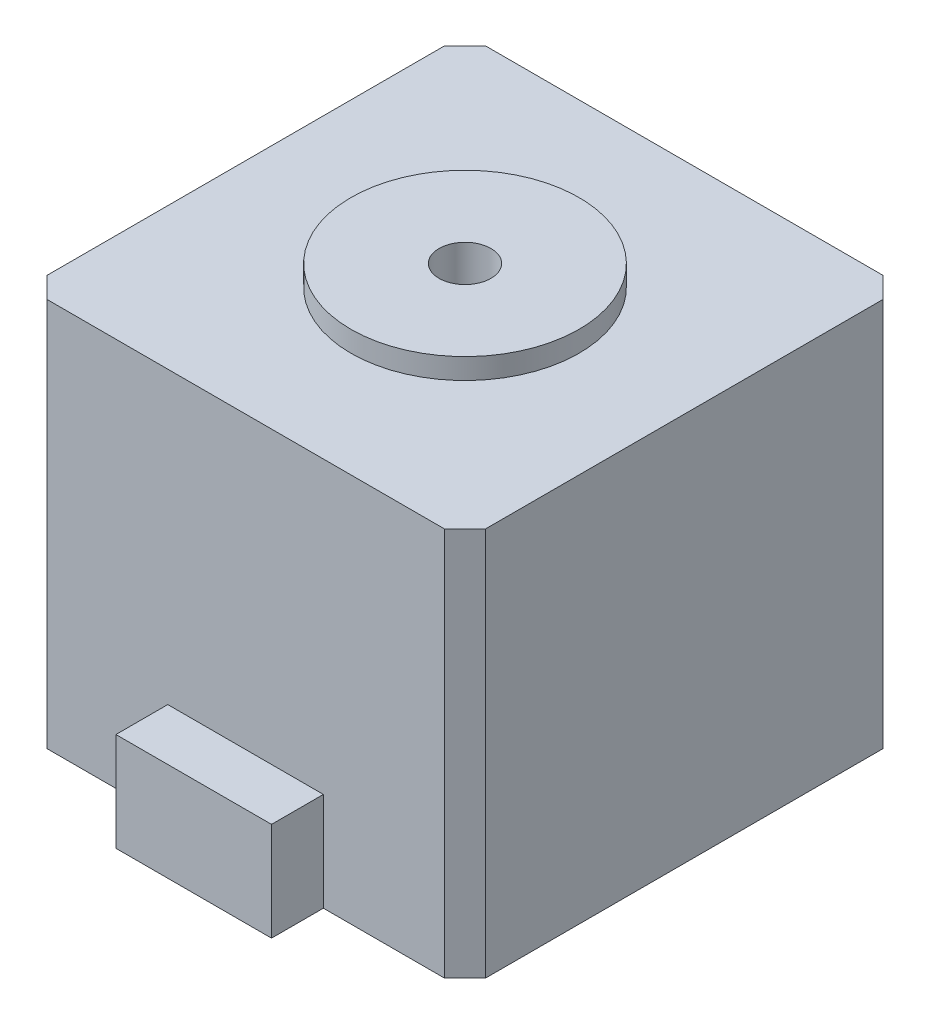
SolidWorks part; units mm, degrees
ref_plane "Front Plane" through (0, 0, 0) normal (0, 0, 1) x (1, 0, 0)
ref_plane "Top Plane" through (0, 0, 0) normal (0, 1, 0) x (1, 0, 0)
ref_plane "Right Plane" through (0, 0, 0) normal (1, 0, 0) x (0, 0, -1)
sketch "Sketch1" plane through (0, 0, 0) normal (0, 1, 0) x (1, 0, 0)
  line L1 (0, 0) -> (42.3, 0)
  line L2 (0, 0) -> (0, 42.3)
  line L3 (0, 42.3) -> (42.3, 42.3)
  line L4 (42.3, 0) -> (42.3, 42.3)
  dimension "D1" = 42.3
  dimension "D2" = 42.3
extrude "Boss-Extrude1" add sketch "Sketch1" along normal blind 37.5
chamfer "Chamfer2" distance 2 angle 45 4 edges at (42.3, 18.75, -42.3) (0, 18.75, -42.3) (0, 18.75, 0) (42.3, 18.75, 0)
sketch "Sketch2" plane through (0, 37.5, 0) normal (0, 1, 0) x (1, 0, 0)
  line L0 (21.15, 38.0694) -> (21.15, -5.6443) construction
  line L1 (0, 40.3) -> (0, 2) construction
  line L2 (42.3, 2) -> (42.3, 40.3) construction
  line L3 (38.6993, 21.15) -> (67.8251, 21.15) construction
  line L4 (40.3, 42.3) -> (2, 42.3) construction
  line L5 (2, 0) -> (40.3, 0) construction
  circle A0 centre (21.15, 21.15) radius 11
  dimension "D1" = 22
extrude "Boss-Extrude2" add sketch "Sketch2" along normal blind 2
sketch "Sketch3" plane through (0, 39.5, 0) normal (0, 1, 0) x (1, 0, 0)
  line L0 (21.15, 36.633) -> (21.15, 13.792) construction
  line L1 (0, 40.3) -> (0, 2) construction
  line L2 (42.3, 2) -> (42.3, 40.3) construction
  line L3 (2.8497, 21.15) -> (14.3227, 21.15) construction
  line L4 (40.3, 42.3) -> (2, 42.3) construction
  line L5 (2, 0) -> (40.3, 0) construction
  circle A1 centre (21.15, 21.15) radius 2.5
  dimension "D1" = 5
extrude "Cut-Extrude2" cut sketch "Sketch3" against normal blind 20
sketch "Sketch5" plane through (0, 0, 0) normal (0, 0, 1) x (1, 0, 0)
  line L0 (2, 0) -> (40.3, 0) construction
  line L1 (13.65, 0) -> (28.65, 0)
  line L2 (13.65, 0) -> (13.65, 9.5)
  line L3 (13.65, 9.5) -> (28.65, 9.5)
  line L4 (28.65, 0) -> (28.65, 9.5)
  line L5 (21.15, 17.9991) -> (21.15, 41.4455) construction
  line L6 (2, 37.5) -> (2, 0) construction
  line L7 (40.3, 0) -> (40.3, 37.5) construction
  dimension "D1" = 9.5
  dimension "D2" = 15
extrude "Boss-Extrude4" add sketch "Sketch5" along normal blind 5
